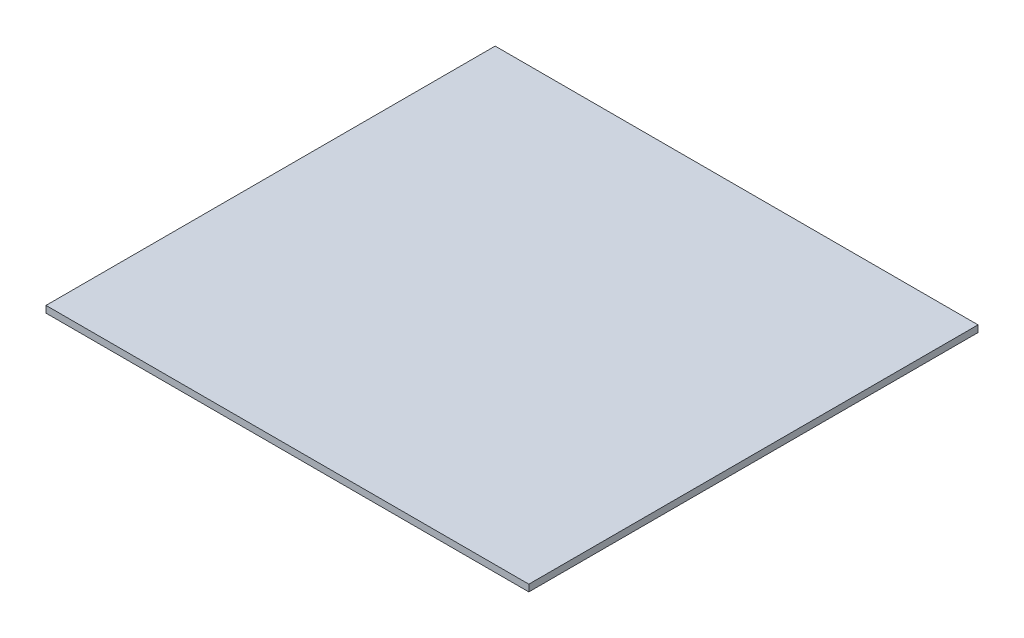
SolidWorks part; units mm, degrees
material "Glass"
ref_plane "Front Plane" through (0, 0, 0) normal (0, 0, 1) x (1, 0, 0)
ref_plane "Top Plane" through (0, 0, 0) normal (0, 1, 0) x (1, 0, 0)
ref_plane "Right Plane" through (0, 0, 0) normal (1, 0, 0) x (0, 0, -1)
sketch "Sketch1" plane through (0, 0, 0) normal (0, 1, 0) x (1, 0, 0)
  line L1 (-215, -200) -> (215, -200)
  line L2 (-215, -200) -> (-215, 200)
  line L3 (-215, 200) -> (215, 200)
  line L4 (215, -200) -> (215, 200)
  line L5 (-215, -200) -> (215, 200) construction
  line L6 (-215, 200) -> (215, -200) construction
  point P0 (0, 0)
  dimension "D1" = 430
  dimension "D2" = 400
extrude "Boss-Extrude1" add sketch "Sketch1" along normal mid plane 6
equation "\"width\"= 430"
equation "\"height\"= 400"
equation "\"thick\"= 6"
equation "\"D2@Sketch1\"=\"height\""
equation "\"D1@Sketch1\"=\"width\""
equation "\"D1@Boss-Extrude1\"=\"thick\""
